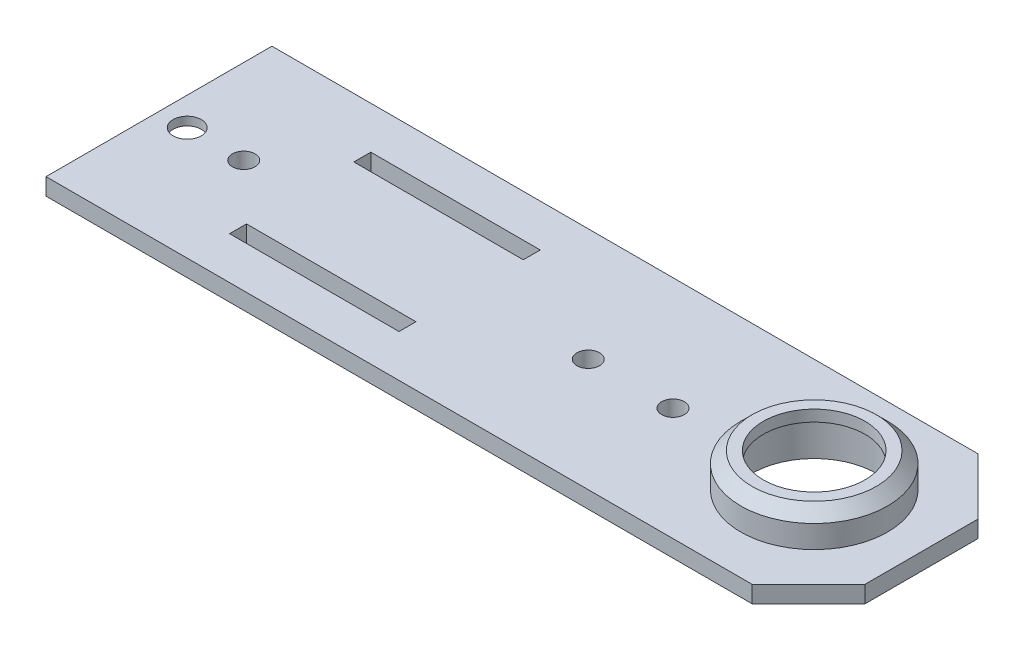
SolidWorks part; units mm, degrees
ref_plane "Alzado" through (0, 0, 0) normal (0, 0, 1) x (1, 0, 0)
ref_plane "Planta" through (0, 0, 0) normal (0, 1, 0) x (1, 0, 0)
ref_plane "Vista lateral" through (0, 0, 0) normal (1, 0, 0) x (0, 0, -1)
sketch "Croquis1" plane through (0, 0, 0) normal (0, 1, 0) x (1, 0, 0)
  line L1 (-67.5, -20) -> (67.5, -20)
  line L2 (-67.5, -20) -> (-67.5, -10)
  line L3 (-67.5, 20) -> (67.5, 20)
  line L4 (67.5, -20) -> (67.5, 20)
  line L5 (-67.5, -20) -> (67.5, 20) construction
  line L6 (-67.5, 20) -> (67.5, -20) construction
  line L9 (-67.5, 10) -> (-67.5, 20)
  line L10 (-67.5, -10) -> (-57.5, -10)
  line L11 (-42.5, 9.5) -> (-12.5, 9.5)
  line L12 (-42.5, 9.5) -> (-42.5, 12.5)
  line L13 (-42.5, 12.5) -> (-12.5, 12.5)
  line L14 (-12.5, 9.5) -> (-12.5, 12.5)
  line L15 (-42.5, 9.5) -> (-12.5, 12.5) construction
  line L16 (-42.5, 12.5) -> (-12.5, 9.5) construction
  line L17 (-42.5, -12.5) -> (-12.5, -12.5)
  line L18 (-42.5, -12.5) -> (-42.5, -9.5)
  line L19 (-42.5, -9.5) -> (-12.5, -9.5)
  line L20 (-12.5, -12.5) -> (-12.5, -9.5)
  line L21 (-42.5, -12.5) -> (-12.5, -9.5) construction
  line L22 (-42.5, -9.5) -> (-12.5, -12.5) construction
  line L24 (-57.5, 10) -> (-67.5, 10)
  line L25 (-57.5, -10) -> (-57.5, 10)
  line L26 (0, 0) -> (67.5, 0) construction
  circle A2 centre (48.5, 0) radius 11
  circle A3 centre (-52.5, 0) radius 2
  circle A4 centre (23.5, 0) radius 2
  circle A5 centre (8.5, 0) radius 2
  point P0 (0, 0)
  point P16 (0, 0)
  point P20 (-27.5, 11)
  point P26 (0, 0)
  point P27 (0, 0)
  point P28 (-27.5, -11)
  dimension "D6" = 15
  dimension "D7" = 22
  dimension "D11" = 10
  dimension "D12" = 4
  dimension "D5" = 19
  dimension "D1" = 40
  dimension "D2" = 135
  dimension "D3" = 10
  dimension "D4" = 20
  dimension "D8" = 30
  dimension "D9" = 3
  dimension "D10" = 40
  dimension "D13" = 12.5
  dimension "D14" = 12.5
  dimension "D15" = 25
extrude "Saliente-Extruir1" add sketch "Croquis1" along normal blind 3
sketch "Croquis2" plane through (0, 3, 0) normal (0, 1, 0) x (1, 0, 0)
  circle A0 centre (48.5, 0) radius 11
  circle A1 centre (48.5, 0) radius 13
  dimension "D1" = 2
extrude "Saliente-Extruir2" add sketch "Croquis2" along normal blind 4
sketch "Croquis3" plane through (0, 7, 0) normal (0, 1, 0) x (1, 0, 0)
  circle A0 centre (48.5, 0) radius 13
  circle A1 centre (48.5, 0) radius 9
  dimension "D1" = 18
extrude "Saliente-Extruir3" add sketch "Croquis3" along normal blind 2
chamfer "Chaflán1" distance 2 angle 45 1 edges at (48.5, 9, 13)
chamfer "Chaflán2" distance 10 angle 45 2 edges at (67.5, 1.5, -20) (67.5, 1.5, 20)
sketch "Croquis4" plane through (0, 3, 0) normal (0, 1, 0) x (1, 0, 0)
  line L0 (-57.5, 0) -> (-67.5, 0) construction
  line L5 (-67.5, 10) -> (-57.5, 10)
  line L6 (-67.5, 10) -> (-67.5, -10)
  line L7 (-67.5, -10) -> (-57.5, -10)
  line L8 (-57.5, 10) -> (-57.5, -10)
  circle A0 centre (-62.5, 0) radius 2.5
  dimension "D1" = 5
extrude "Saliente-Extruir4" add sketch "Croquis4" against normal blind 1.5
